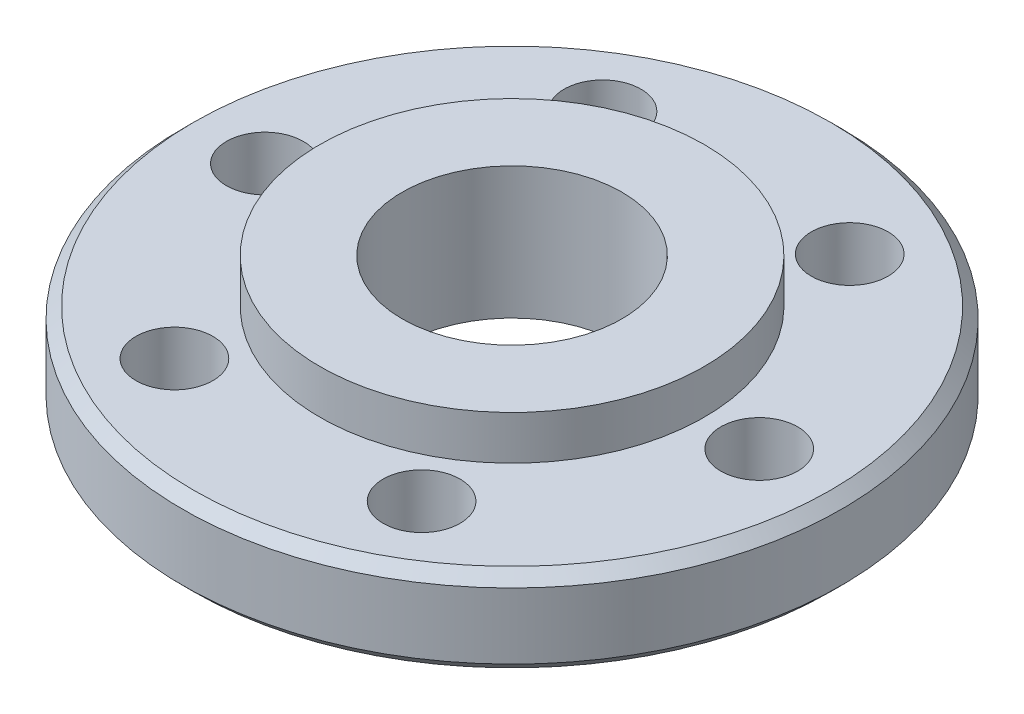
SolidWorks part; units mm, degrees
ref_plane "前视基准面" through (0, 0, 0) normal (0, 0, 1) x (1, 0, 0)
ref_plane "上视基准面" through (0, 0, 0) normal (0, 1, 0) x (1, 0, 0)
ref_plane "右视基准面" through (0, 0, 0) normal (1, 0, 0) x (0, 0, -1)
other "Configuration Table"
sketch "草图1" plane through (0, 0, 0) normal (0, 0, 1) x (1, 0, 0)
  line L0 (0, -10) -> (0, 30) construction
  line L1 (20, 0) -> (58, 0)
  line L2 (58, 0) -> (60, 2)
  line L3 (60, 2) -> (60, 14)
  line L4 (60, 14) -> (58, 16)
  line L5 (58, 16) -> (35, 16)
  line L6 (35, 16) -> (35, 24)
  line L7 (35, 24) -> (20, 24)
  line L8 (20, 24) -> (20, 0)
revolve "旋转1" add sketch "草图1" angle 360 about L0
sketch "草图2" plane through (0, 0, 0) normal (0, 1, 0) x (1, 0, 0)
  circle A0 centre (45, 0) radius 7
extrude "切除-拉伸1" cut sketch "草图2" along normal through all
pattern_circular "阵列(圆周)1" count 6 over 360 about axis through (0, 0, 0) along (0, 1, 0) of "切除-拉伸1"
